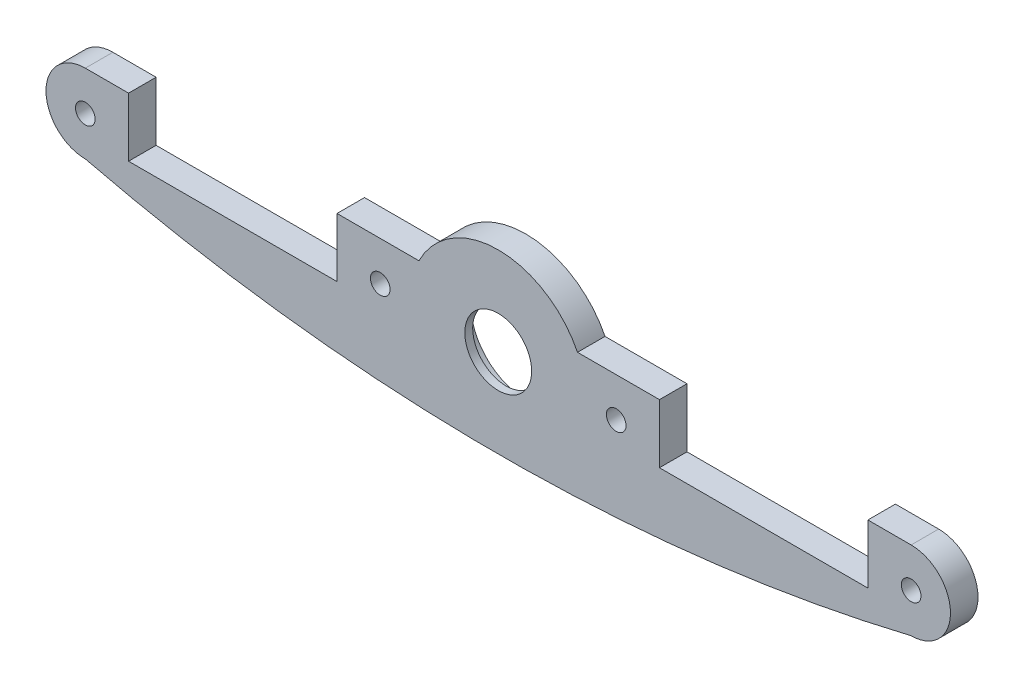
SolidWorks part; units mm, degrees
ref_plane "前视基准面" through (0, 0, 0) normal (0, 0, 1) x (1, 0, 0)
ref_plane "上视基准面" through (0, 0, 0) normal (0, 1, 0) x (1, 0, 0)
ref_plane "右视基准面" through (0, 0, 0) normal (1, 0, 0) x (0, 0, -1)
other "Configuration Table"
sketch "草图1" plane through (0, 0, 0) normal (0, 0, 1) x (1, 0, 0)
  line L0 (105, 0) -> (-105, 0) construction
  line L1 (105, -10) -> (-105, -10)
  line L2 (105, 10) -> (-105, 10)
  line L4 (0, 0) -> (0, 54.8954) construction
  line L6 (0, 0) -> (133.0814, 0) construction
  circle A1 centre (0, 0) radius 7.5 construction
  circle A2 centre (0, 0) radius 22.5
  arc A3 (105, -10) -> (105, 10) centre (105, 0) ccw
  arc A4 (-105, 10) -> (-105, -10) centre (-105, 0) ccw
  circle A5 centre (0, 0) radius 8.5
  point P6 (0, 0)
  dimension "D1" = 15
  dimension "D3" = 10
  dimension "D4" = 1
  dimension "D2" = 210
extrude "凸台-拉伸1" add sketch "草图1" against normal blind 7
sketch "草图3" plane through (0, 0, -7) normal (0, 0, -1) x (-1, 0, 0)
  circle A1 centre (0, 0) radius 14
  dimension "D1" = 28
extrude "切除-拉伸2" cut sketch "草图3" against normal blind 5
sketch "草图4" plane through (0, 0, -7) normal (0, 0, 1) x (1, 0, 0)
  line L0 (0, 0) -> (169.9754, 0) construction
  line L1 (0, 0) -> (0, 91.6973) construction
  circle A0 centre (30, 0) radius 2.5
  circle A1 centre (105, 0) radius 2.5
  circle A2 centre (-105, 0) radius 2.5
  circle A3 centre (-30, 0) radius 2.5
  dimension "D1" = 5
  dimension "D2" = 75
  dimension "D3" = 30
extrude "切除-拉伸3" cut sketch "草图4" along normal up to next
sketch "草图6" plane through (0, 0, -7) normal (0, 0, -1) x (-1, 0, 0)
  line L0 (-97, -29.5) -> (-38, -29.5) construction
  line L1 (-38, -29.5) -> (-38, -6) construction
  line L2 (-97, -6) -> (-97, -29.5) construction
  line L3 (-97, -29.5) -> (-38, -29.5) construction
  line L4 (-38, -29.5) -> (-38, -6) construction
  line L5 (-97, -6) -> (-97, -29.5) construction
  line L6 (-97, 29.5) -> (-97, 6) construction
  line L7 (-38, 6) -> (-38, 29.5) construction
  line L8 (-38, 29.5) -> (-97, 29.5) construction
  line L9 (-97, 29.5) -> (-97, 6) construction
  line L10 (-38, 6) -> (-38, 29.5) construction
  line L11 (-38, 29.5) -> (-97, 29.5) construction
  line L12 (-76, 23.5) -> (-76, 15.5) construction
  line L13 (-76, 15.5) -> (-63, 15.5) construction
  line L14 (-63, 15.5) -> (-63, 23.5) construction
  line L15 (-63, 23.5) -> (-76, 23.5) construction
  line L16 (-76, 23.5) -> (-76, 15.5) construction
  line L17 (-76, 15.5) -> (-63, 15.5) construction
  line L18 (-63, 15.5) -> (-63, 23.5) construction
  line L19 (-63, 23.5) -> (-76, 23.5) construction
  line L20 (-105, 10) -> (-20.1556, 10) construction
  line L21 (-105, 10) -> (-20.1556, 10) construction
  line L22 (-94, 10) -> (-94, -5)
  line L23 (-94, -5) -> (-41, -5)
  line L24 (-41, -5) -> (-41, 10)
  line L25 (-94, 10) -> (-41, 10)
  line L26 (0, 0) -> (0, 46.9075) construction
  line L27 (94, 10) -> (94, -5)
  line L28 (94, -5) -> (41, -5)
  line L29 (41, -5) -> (41, 10)
  line L30 (94, 10) -> (41, 10)
  dimension "D1" = 15
  dimension "D2" = 3
  dimension "D3" = 3
extrude "切除-拉伸5" cut sketch "草图6" against normal up to next
sketch "草图7" plane through (0, 0, -7) normal (0, 0, -1) x (-1, 0, 0)
  line L0 (20.1556, -10) -> (105, -10) construction
  line L1 (-105, -10) -> (-20.1556, -10) construction
  line L2 (20.1556, -10) -> (105, -10)
  line L3 (-105, -10) -> (-20.1556, -10)
  line L4 (0, 0) -> (0, 68.3649) construction
  arc A0 (105, -10) -> (105, 10) centre (105, 0) ccw construction
  arc A1 (-105, 10) -> (-105, -10) centre (-105, 0) ccw construction
  arc A2 (-20.1556, -10) -> (20.1556, -10) centre (0, 0) ccw construction
  arc A3 (105, -10) -> (105, 10) centre (105, 0) ccw construction
  arc A4 (-105, 10) -> (-105, -10) centre (-105, 0) ccw construction
  arc A5 (-20.1556, -10) -> (20.1556, -10) centre (0, 0) ccw
  arc A6 (-105, -10) -> (105, -10) centre (0, 424.75) ccw
  line M14 (-105, -10) -> (-20.1556, -10)
  arc M15 (-20.1556, -10) -> (20.1556, -10) centre (0, 0) ccw
  line M16 (20.1556, -10) -> (105, -10)
extrude "凸台-拉伸2" add sketch "草图7" against normal up to surface (7 mm away) contours A6 M14 M15 | A5 A6 M16 up to face at (0, 1.25, 0)
